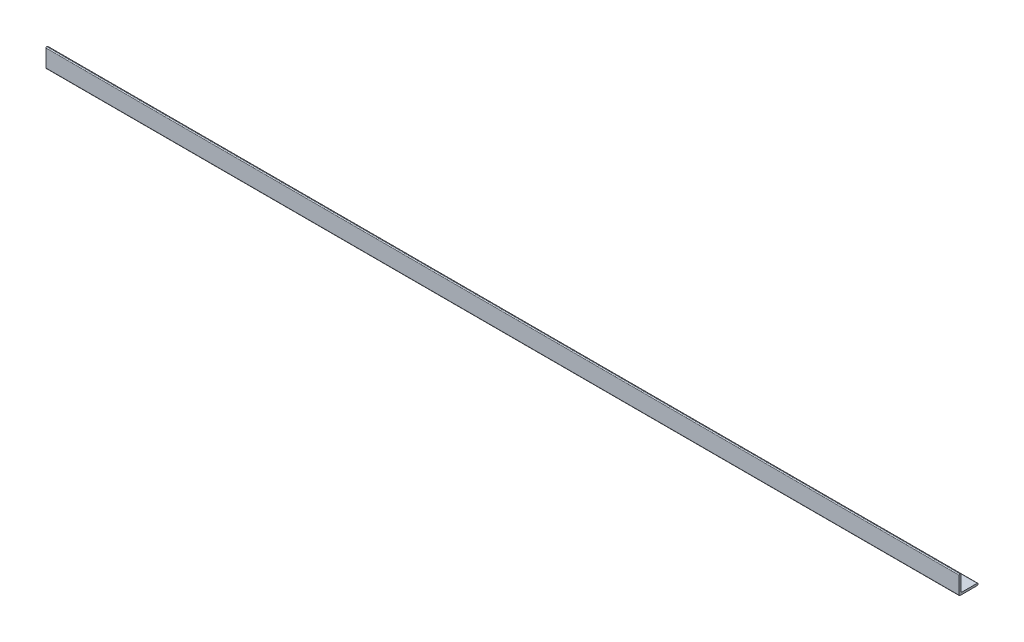
SolidWorks part; units mm, degrees
ref_plane "Front Plane" through (0, 0, 0) normal (0, 0, 1) x (1, 0, 0)
ref_plane "Top Plane" through (0, 0, 0) normal (0, 1, 0) x (1, 0, 0)
ref_plane "Right Plane" through (0, 0, 0) normal (1, 0, 0) x (0, 0, -1)
sketch "Sketch1" plane through (0, 0, 0) normal (0, 1, 0) x (1, 0, 0)
  line L1 (-544, 11.25) -> (544, 11.25)
  line L2 (-544, 11.25) -> (-544, -11.25)
  line L3 (-544, -11.25) -> (544, -11.25)
  line L4 (544, 11.25) -> (544, -11.25)
  line L5 (-544, 11.25) -> (544, -11.25) construction
  line L6 (-544, -11.25) -> (544, 11.25) construction
  point P0 (0, 0)
  dimension "D1" = 1088
  dimension "D2" = 22.5
extrude "Boss-Extrude1" add sketch "Sketch1" along normal blind 2.5
sketch "Sketch2" plane through (0, 2.5, 0) normal (0, 1, 0) x (1, 0, 0)
  line L0 (-544, 11.25) -> (-544, -11.25) construction
  line L1 (544, -11.25) -> (-544, -11.25)
  line L2 (544, -11.25) -> (544, -8.75)
  line L3 (544, -8.75) -> (-544, -8.75)
  line L4 (-544, -11.25) -> (-544, -8.75)
  dimension "D1" = 2.5
extrude "Boss-Extrude2" add sketch "Sketch2" along normal blind 20
fillet "Fillet1" radius 1 6 edges at (0, 0, 11.25) (0, 0, -11.25) (0, 2.5, -11.25) (0, 22.5, 11.25) (0, 22.5, 8.75) (0, 2.5, 8.75)
